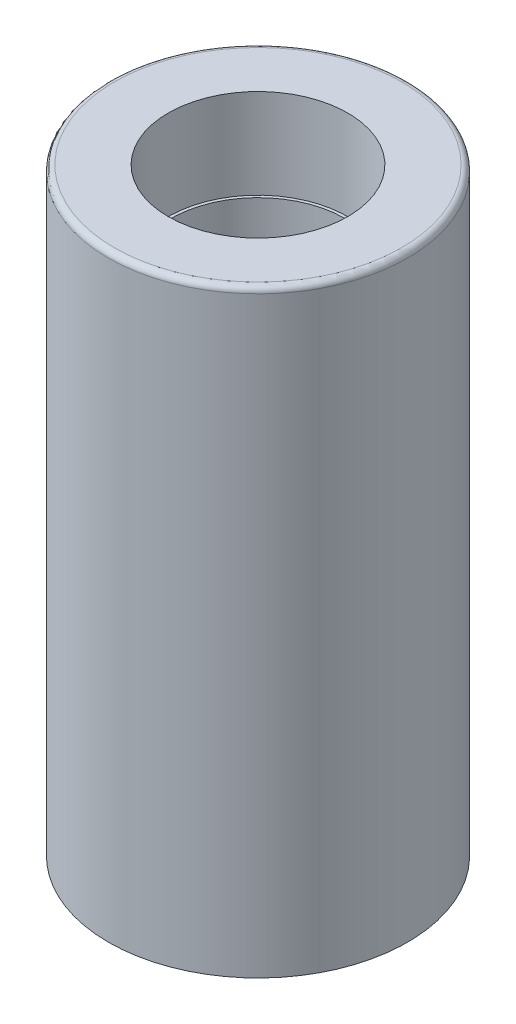
SolidWorks part; units mm, degrees
ref_plane "Ebene vorne" through (0, 0, 0) normal (0, 0, 1) x (1, 0, 0)
ref_plane "Ebene oben" through (0, 0, 0) normal (0, 1, 0) x (1, 0, 0)
ref_plane "Ebene rechts" through (0, 0, 0) normal (1, 0, 0) x (0, 0, -1)
sketch "Skizze1" plane through (0, 0, 0) normal (0, 1, 0) x (1, 0, 0)
  circle A0 centre (0, 0) radius 5
extrude "Aufsatz-Linear austragen1" add sketch "Skizze1" along normal blind 20
sketch "Skizze2" plane through (0, 20, 0) normal (0, 1, 0) x (1, 0, 0)
  circle A0 centre (0, 0) radius 2.9
extrude "Schnitt-Linear austragen1" cut sketch "Skizze2" against normal blind 20
sketch "Skizze3" plane through (0, 20, 0) normal (0, 1, 0) x (1, 0, 0)
  circle A0 centre (0, 0) radius 3
extrude "Schnitt-Linear austragen2" cut sketch "Skizze3" against normal blind 3
fillet "Verrundung1" radius 0.2 1 edges at (0, 20, 5)
